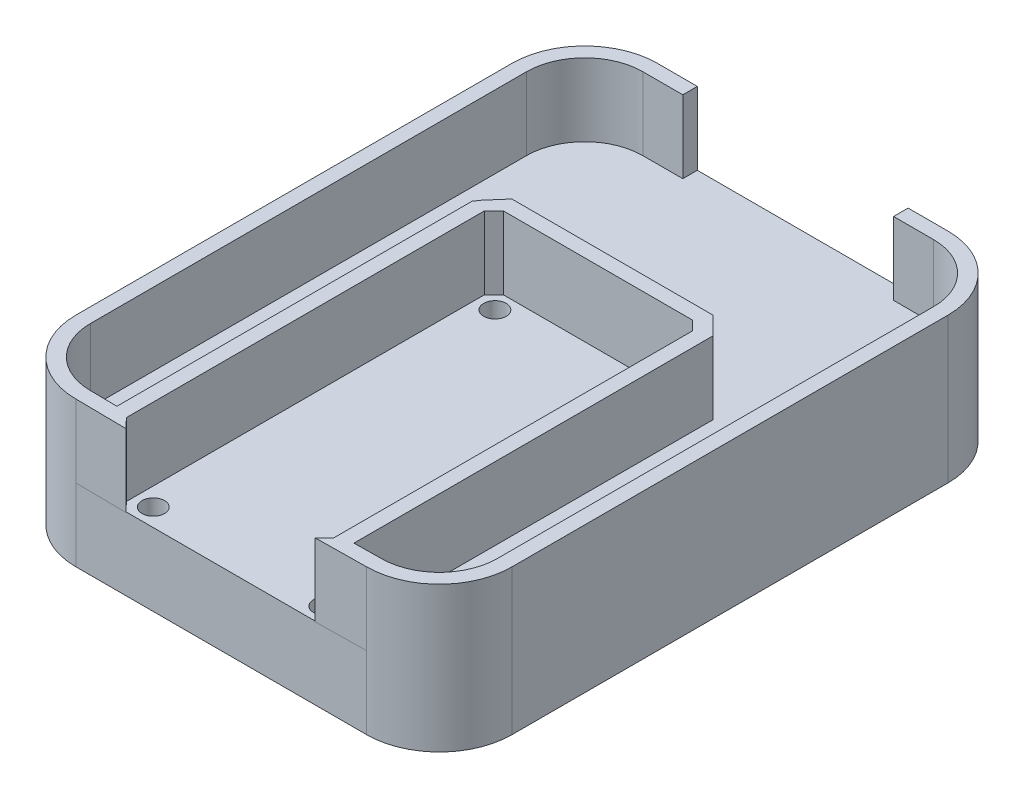
SolidWorks part; units mm, degrees
ref_plane "Front Plane" through (0, 0, 0) normal (0, 0, 1) x (1, 0, 0)
ref_plane "Top Plane" through (0, 0, 0) normal (0, 1, 0) x (1, 0, 0)
ref_plane "Right Plane" through (0, 0, 0) normal (1, 0, 0) x (0, 0, -1)
sketch "Sketch1" plane through (0, 0, 0) normal (0, 1, 0) x (1, 0, 0)
  line L1 (30, -40) -> (-30, -40)
  line L2 (30, -40) -> (30, 40)
  line L3 (30, 40) -> (-30, 40)
  line L4 (-30, -40) -> (-30, 40)
  line L5 (30, -40) -> (-30, 40) construction
  line L6 (30, 40) -> (-30, -40) construction
  point P0 (0, 0)
  dimension "D1" = 80
  dimension "D2" = 60
extrude "Boss-Extrude1" add sketch "Sketch1" along normal mid plane 10
fillet "Fillet1" radius 10 4 edges at (-30, 0, -40) (30, 0, -40) (30, 0, 40) (-30, 0, 40)
sketch "Sketch3" plane through (0, 5, 0) normal (0, 1, 0) x (1, 0, 0)
  circle A0 centre (-11.8, 9.45) radius 1.55
  circle A1 centre (11.8, 9.45) radius 1.55
  circle A2 centre (-11.8, -37.55) radius 1.55
  circle A3 centre (11.8, -37.55) radius 1.55
extrude "Cut-Extrude11" cut sketch "Sketch3" against normal blind 10
sketch "Sketch5" plane through (0, 5, 0) normal (0, 1, 0) x (1, 0, 0)
  line L0 (-14.3149, 10.5125) -> (-14.3149, -38.7484)
  line L1 (-14.3149, -38.7484) -> (-13.0142, -40.0882)
  line L2 (-13.0142, -40.0882) -> (12.9865, -40.0882)
  line L3 (12.9865, -40.0882) -> (14.2852, -38.7894)
  line L4 (14.2852, -38.7894) -> (14.3, 10.5076)
  line L5 (14.3, -38.7) -> (14.3, 10.6) construction
  line L6 (14.3, 10.5076) -> (12.9865, 11.8211)
  line L7 (12.9865, 11.8211) -> (-13.0142, 11.8211)
  line L8 (-13.0142, 11.8211) -> (-14.3137, 10.5162)
  line L9 (-14.3149, 10.5125) -> (-14.3137, 10.5162)
  line L10 (-14.5, 40) -> (14.5, 40)
  line L11 (20, 40) -> (-20, 40) construction
  line L12 (-14.5, 39) -> (-14.5, 40) construction
  line L13 (14.5, 39) -> (14.5, 40) construction
  line L14 (-16.3149, 10.8191) -> (-16.3149, -38.7484)
  line L18 (16.3002, -38.7894) -> (16.3002, 11.3358)
  line L19 (16.3002, 11.3358) -> (13.8149, 13.8211)
  line L20 (13.8149, 13.8211) -> (-13.8451, 13.8211)
  line L21 (-13.8451, 13.8211) -> (-15.8426, 11.5159)
  line L22 (-16.3149, 10.8191) -> (-15.8426, 11.5159)
  line L23 (-16.3149, -38.7484) -> (-14.3149, -38.7484)
  line L24 (14.2852, -38.7894) -> (16.3002, -38.7894)
  point P14 (-15.8426, 11.5159)
  point P15 (0, 0)
sketch "Sketch6" plane through (0, 5, 0) normal (0, 1, 0) x (1, 0, 0)
  line L0 (30, -30) -> (30, 30) construction
  line L1 (-30, 30) -> (-30, -30) construction
  line L2 (30, -30) -> (30, 30)
  line L3 (-30, 30) -> (-30, -30)
  line L4 (-20, 40) -> (-14.5, 40)
  line L5 (14.5, 40) -> (20, 40)
  line L6 (-20, -40) -> (-13.0142, -40.0882)
  line L7 (12.9865, -40.0882) -> (20, -40)
  line L8 (14.3011, -38.0715) -> (19.9881, -38)
  line L9 (28, -30) -> (28, 30)
  line L10 (14.5, 38) -> (20, 38)
  line L11 (-20, 38) -> (-14.5, 38)
  line L12 (-28, 30) -> (-28, -30)
  line L13 (12.9613, -38.0883) -> (19.9881, -38) construction
  line L14 (-19.9881, -38) -> (-14.3149, -38.0716)
  line L15 (14.3011, -38.0715) -> (14.2854, -38.0715)
  line L16 (-14.3149, 10.5125) -> (-14.3149, -38.7484) construction
  line L17 (14.2852, -38.7894) -> (14.3, 10.5076) construction
  line L18 (-19.9881, -38) -> (-12.989, -38.0883) construction
  line L19 (14.3011, -38.0715) -> (14.2852, -38.7894)
  line L20 (14.2852, -38.7894) -> (12.9865, -40.0882)
  line L21 (-14.3149, -38.0716) -> (-14.3149, -38.7484)
  line L22 (-14.3149, -38.7484) -> (-13.0142, -40.0882)
  line L23 (-14.5, 38) -> (-14.5, 40)
  line L24 (14.5, 40) -> (14.5, 38)
  arc A0 (30, 30) -> (20, 40) centre (20, 30) ccw construction
  arc A1 (20, -40) -> (30, -30) centre (20, -30) ccw construction
  arc A2 (-30, -30) -> (-20, -40) centre (-20, -30) ccw construction
  arc A3 (-20, 40) -> (-30, 30) centre (-20, 30) ccw construction
  arc A4 (30, 30) -> (20, 40) centre (20, 30) ccw
  arc A5 (20, -40) -> (30, -30) centre (20, -30) ccw
  arc A6 (-30, -30) -> (-20, -40) centre (-20, -30) ccw
  arc A7 (-20, 40) -> (-30, 30) centre (-20, 30) ccw
  arc A8 (19.9881, -38) -> (28, -30) centre (20, -30) ccw
  arc A9 (28, 30) -> (20, 38) centre (20, 30) ccw
  arc A10 (-20, 38) -> (-28, 30) centre (-20, 30) ccw
  arc A11 (-28, -30) -> (-19.9881, -38) centre (-20, -30) ccw
  point P37 (-14.3149, -38.0716)
  dimension "D1" = 2
  dimension "D2" = 2
extrude "Boss-Extrude2" add sketch "Sketch6" along normal blind 10 contours L12 A11 L14 L21 L22 L6 A6 L3 A7 L4 L23 L11 A10 | L8 A8 L9 A9 L10 L24 L5 A4 L2 A5 L7 L20 L19
extrude "Boss-Extrude3" add sketch "Sketch5" along normal blind 10 contours L4 L24 L18 L19 L20 L21 L22 L14 L23 L0 L9 L8 L7 L6
